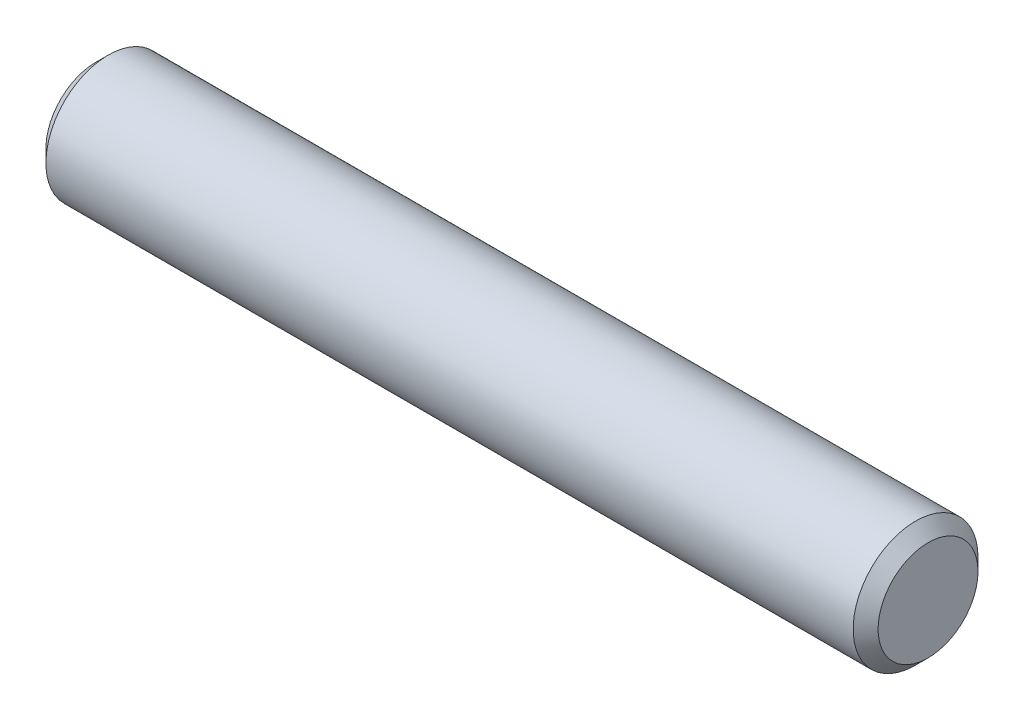
SolidWorks part; units mm, degrees
ref_plane "Front" through (0, 0, 0) normal (0, 0, 1) x (1, 0, 0)
ref_plane "Top" through (0, 0, 0) normal (0, 1, 0) x (1, 0, 0)
ref_plane "Right" through (0, 0, 0) normal (1, 0, 0) x (0, 0, -1)
sketch "Sketch1" plane through (0, 0, 0) normal (0, 0, 1) x (1, 0, 0)
  line L0 (-15.875, 0) -> (15.875, 0) construction
  line L1 (15.875, 2.3813) -> (15.875, -2.3813) construction
  line L2 (-15.875, 2.3813) -> (-15.875, -2.3813) construction
  dimension "Length" = 31.75
  dimension "Diameter" = 4.7625
sketch "Sketch2" plane through (0, 0, 0) normal (1, 0, 0) x (0, 0, -1)
  circle A0 centre (0, 0) radius 2.3813
extrude "Extrude1" add sketch "Sketch2" against normal up to vertex (15.875 mm away) and the other way up to vertex (15.875 mm away) up to point (-15.875, 2.3813, 0) other way up to point (15.875, 2.3813, 0)
chamfer "Chamfer1" distance 0.4763 angle 45 2 edges at (15.875, 0, -2.3813) (-15.875, 0, -2.3813)
equation "\"D1@Chamfer1\" = \"Diameter@Sketch1\"*.1"
